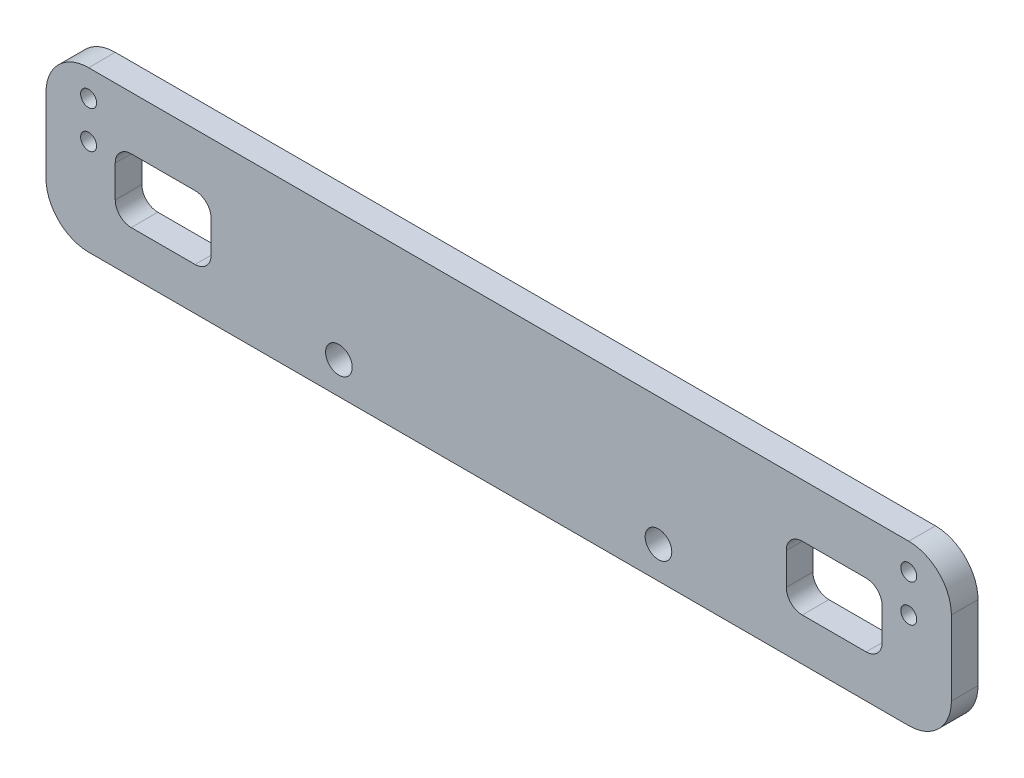
SolidWorks part; units mm, degrees
ref_plane "前视基准面" through (0, 0, 0) normal (0, 0, 1) x (1, 0, 0)
ref_plane "上视基准面" through (0, 0, 0) normal (0, 1, 0) x (1, 0, 0)
ref_plane "右视基准面" through (0, 0, 0) normal (1, 0, 0) x (0, 0, -1)
other "质心 (COM)"
sketch "草图1" plane through (0, 0, 0) normal (0, 0, 1) x (1, 0, 0)
  line L1 (-85, -30) -> (85, -30)
  line L2 (-85, -30) -> (-85, 30)
  line L3 (-85, 30) -> (85, 30)
  line L4 (85, -30) -> (85, 30)
  line L5 (-85, -30) -> (85, 30) construction
  line L6 (-85, 30) -> (85, -30) construction
  circle A0 centre (-77, -8) radius 1.5
  circle A1 centre (-77, -1) radius 1.5
  circle A2 centre (77, -1) radius 1.5
  circle A3 centre (77, -8) radius 1.5
  point P0 (0, 0)
  dimension "D3" = 7
  dimension "D4" = 3
  dimension "D5" = 3
  dimension "D6" = 77
  dimension "D7" = 7
  dimension "D8" = 77
  dimension "D9" = 22
  dimension "D10" = 22
  dimension "D1" = 60
  dimension "D2" = 170
extrude "凸台-拉伸1" add sketch "草图1" along normal blind 5
sketch "草图2" plane through (0, 0, 5) normal (0, 0, 1) x (1, 0, 0)
  line L0 (-85, -30) -> (85, -30) construction
  circle A0 centre (-30, -20) radius 2.5
  circle A1 centre (30, -20) radius 2.5
  dimension "D1" = 30
  dimension "D2" = 30
  dimension "D3" = 5
  dimension "D4" = 5
  dimension "D5" = 10
  dimension "D6" = 10
extrude "切除-拉伸1" cut sketch "草图2" against normal blind 5
sketch "草图3" plane through (0, 0, 5) normal (0, 0, 1) x (1, 0, 0)
  line L0 (-85, 30) -> (85, 30)
  line L1 (85, 30) -> (85, 4)
  line L2 (85, -30) -> (85, 30) construction
  line L3 (85, 4) -> (-85, 4)
  line L4 (-85, 30) -> (-85, -30) construction
  line L5 (-85, 4) -> (-85, 30)
  circle A0 centre (-77, -1) radius 1.5 construction
  dimension "D1" = 5
extrude "切除-拉伸2" cut sketch "草图3" against normal blind 10
sketch "草图4" plane through (0, 0, 5) normal (0, 0, 1) x (1, 0, 0)
  line L0 (-72, -6) -> (-54, -6)
  line L1 (-54, -6) -> (-54, -18)
  line L2 (-54, -18) -> (-72, -18)
  line L3 (-72, -18) -> (-72, -6)
  line L4 (-85, -30) -> (85, -30) construction
  line L5 (-85, 4) -> (-85, -30) construction
  line L6 (0, -30) -> (0, -18)
  line L7 (72, -18) -> (72, -6)
  line L8 (54, -18) -> (72, -18)
  line L9 (54, -6) -> (54, -18)
  line L10 (72, -6) -> (54, -6)
  dimension "D1" = 24
  dimension "D2" = 12
  dimension "D3" = 18
  dimension "D4" = 13
extrude "切除-拉伸3" cut sketch "草图4" against normal blind 10 contours L3 L2 L1 L0 | L7 L10 L9 L8
fillet "圆角1" radius 3 8 edges at (72, -18, 2.5) (72, -6, 2.5) (54, -18, 2.5) (54, -6, 2.5) (-54, -18, 2.5) (-54, -6, 2.5) (-72, -18, 2.5) (-72, -6, 2.5)
sketch "草图5" plane through (0, 0, 5) normal (0, 0, 1) x (1, 0, 0)
  line L0 (-85, -26) -> (85, -26)
  line L1 (-85, 4) -> (-85, -30) construction
  line L2 (85, -30) -> (85, 4) construction
  line L3 (85, -26) -> (85, -30)
  line L4 (85, -30) -> (-85, -30)
  line L5 (-85, -30) -> (-85, -26)
  dimension "D1" = 4
extrude "切除-拉伸4" cut sketch "草图5" against normal through all
fillet "圆角2" radius 8 4 edges at (-85, -26, 2.5) (85, -26, 2.5) (85, 4, 2.5) (-85, 4, 2.5)
